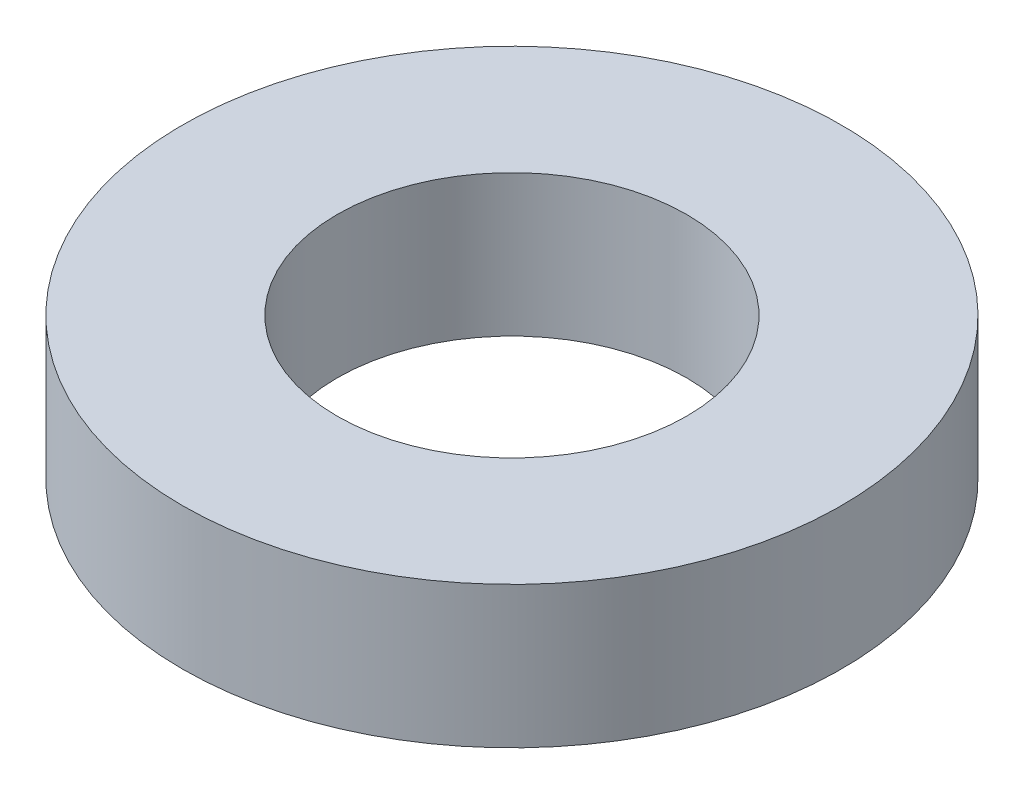
SolidWorks part; units mm, degrees
material "Brass"
ref_plane "Front Plane" through (0, 0, 0) normal (0, 0, 1) x (1, 0, 0)
ref_plane "Top Plane" through (0, 0, 0) normal (0, 1, 0) x (1, 0, 0)
ref_plane "Right Plane" through (0, 0, 0) normal (1, 0, 0) x (0, 0, -1)
sketch "Sketch1" plane through (0, 0, 0) normal (0, 1, 0) x (1, 0, 0)
  circle A0 centre (0, -2.0587) radius 1.8923
  circle A1 centre (0, -2.0587) radius 1.0033
  dimension "D1" = 3.7846
  dimension "D2" = 2.0066
extrude "Boss-Extrude1" add sketch "Sketch1" along normal blind 0.8128
